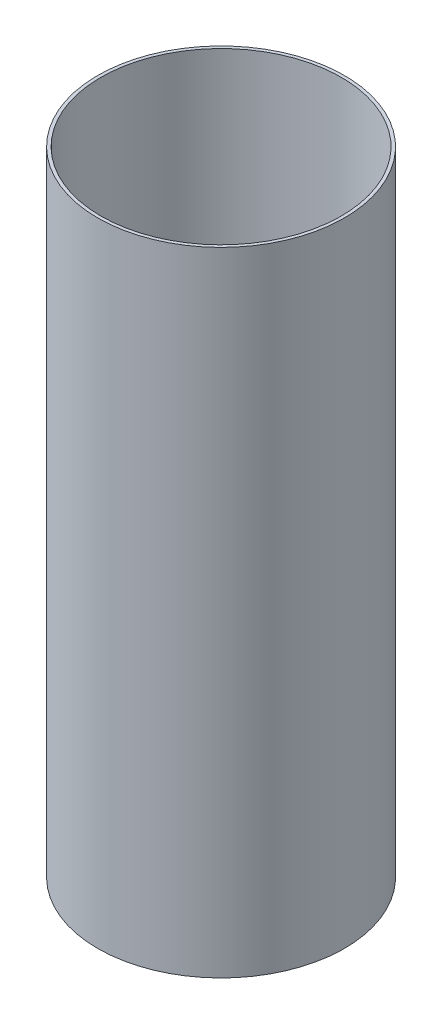
SolidWorks part; units mm, degrees
ref_plane "Спереди" through (0, 0, 0) normal (0, 0, 1) x (1, 0, 0)
ref_plane "Сверху" through (0, 0, 0) normal (0, 1, 0) x (1, 0, 0)
ref_plane "Справа" through (0, 0, 0) normal (1, 0, 0) x (0, 0, -1)
sketch "Эскиз1" plane through (0, 0, 0) normal (0, 1, 0) x (1, 0, 0)
  circle A0 centre (0, 0) radius 76
  circle A1 centre (0, 0) radius 76
  circle A2 centre (0, 0) radius 78
  dimension "D1" = 2
extrude "Бобышка-Вытянуть1" add sketch "Эскиз1" along normal blind 400 contours A2 A0
